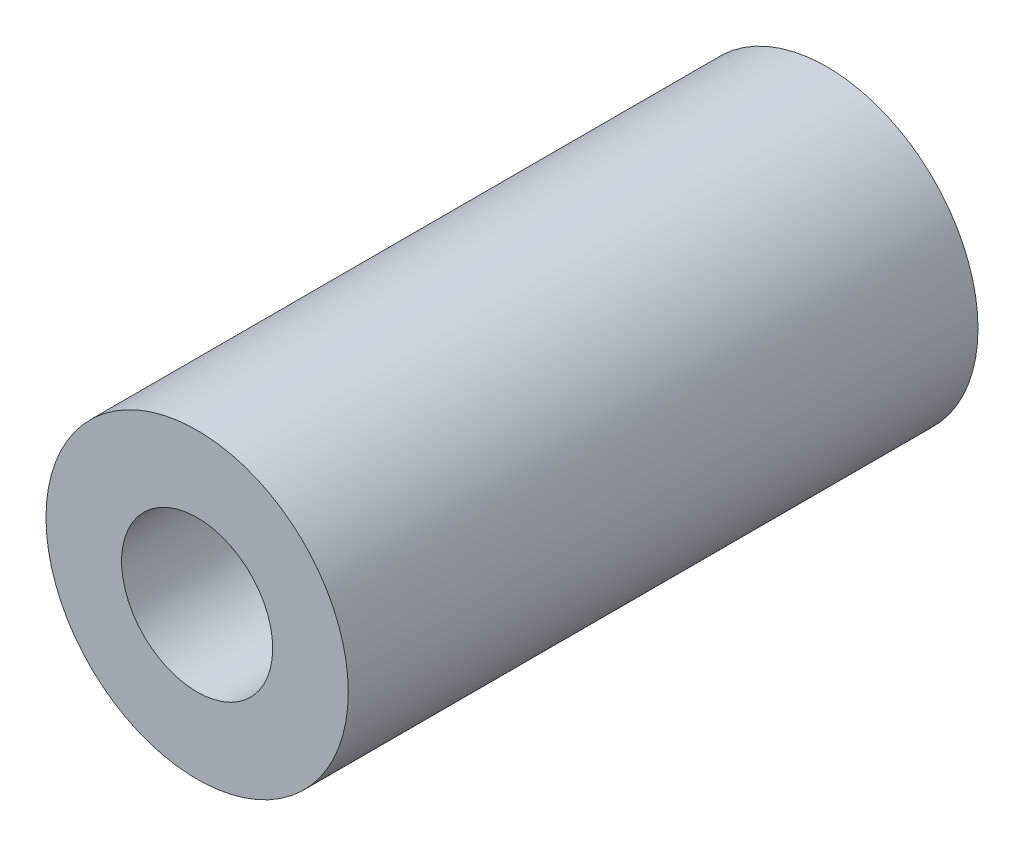
SolidWorks part; units mm, degrees
ref_plane "Front Plane" through (0, 0, 0) normal (0, 0, 1) x (1, 0, 0)
ref_plane "Top Plane" through (0, 0, 0) normal (0, 1, 0) x (1, 0, 0)
ref_plane "Right Plane" through (0, 0, 0) normal (1, 0, 0) x (0, 0, -1)
sketch "Sketch1" plane through (0, 0, 0) normal (0, 0, 1) x (1, 0, 0)
  circle A0 centre (0, 0) radius 6
  circle A1 centre (0, 0) radius 3
  dimension "D1" = 12
  dimension "D2" = 6
extrude "Boss-Extrude2" add sketch "Sketch1" along normal blind 25 contours A0 | A1
